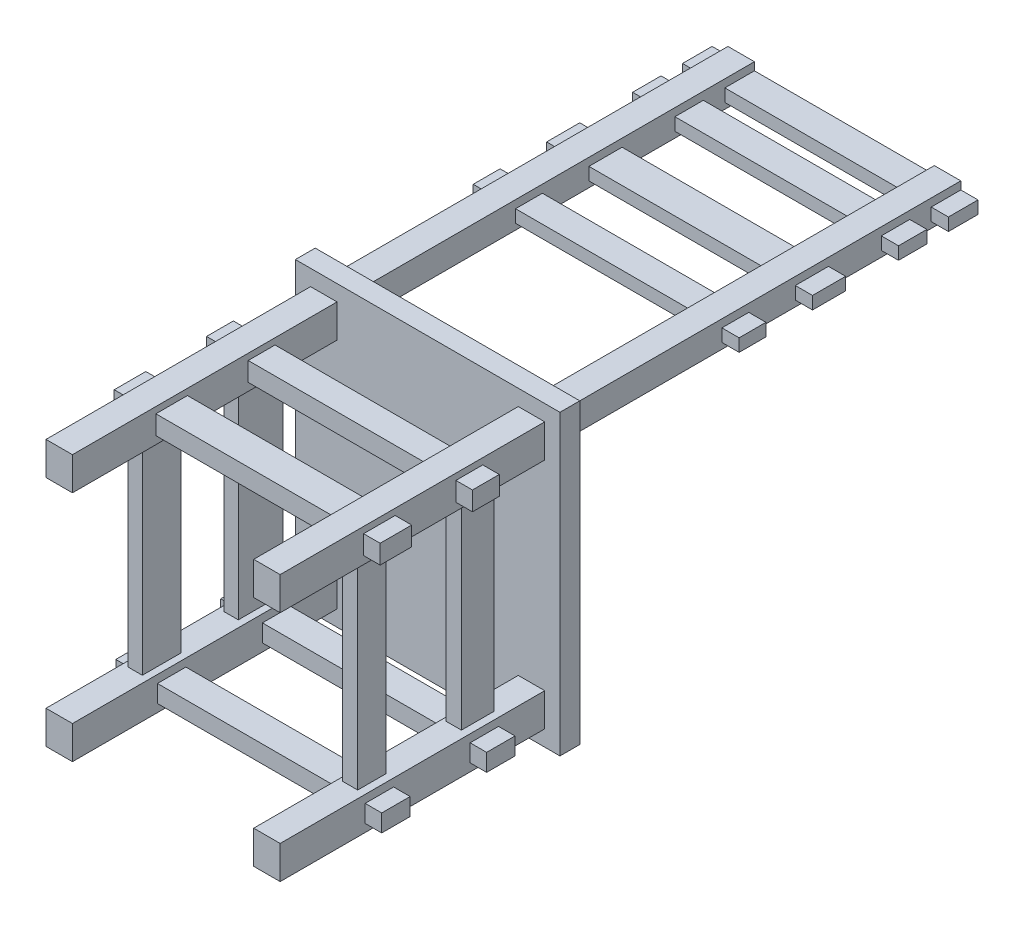
SolidWorks part; units mm, degrees
material "Oak"
ref_plane "Front Plane" through (0, 0, 0) normal (0, 0, 1) x (1, 0, 0)
ref_plane "Top Plane" through (0, 0, 0) normal (0, 1, 0) x (1, 0, 0)
ref_plane "Right Plane" through (0, 0, 0) normal (1, 0, 0) x (0, 0, -1)
sketch "Sketch2" plane through (0, 0, 0) normal (0, 0, 1) x (1, 0, 0)
  line L1 (0, 0) -> (400, 0)
  line L2 (0, 0) -> (0, 450)
  line L3 (0, 450) -> (400, 450)
  line L4 (400, 0) -> (400, 450)
  dimension "D1" = 400
  dimension "D2" = 450
extrude "Boss-Extrude1" add sketch "Sketch2" along normal blind 30
sketch "Sketch3" plane through (0, 0, 30) normal (0, 0, 1) x (1, 0, 0)
  line L0 (0, 450) -> (0, 0) construction
  line L1 (23, 376) -> (63, 376)
  line L2 (23, 376) -> (23, 426)
  line L3 (23, 426) -> (63, 426)
  line L4 (63, 376) -> (63, 426)
  line L5 (23, 376) -> (63, 426) construction
  line L6 (23, 426) -> (63, 376) construction
  line L7 (337, 376) -> (377, 376)
  line L8 (337, 376) -> (337, 426)
  line L9 (337, 426) -> (377, 426)
  line L10 (377, 376) -> (377, 426)
  line L11 (337, 376) -> (377, 426) construction
  line L12 (337, 426) -> (377, 376) construction
  line L13 (377, 74) -> (337, 74)
  line L14 (377, 74) -> (377, 24)
  line L15 (377, 24) -> (337, 24)
  line L16 (337, 74) -> (337, 24)
  line L17 (377, 74) -> (337, 24) construction
  line L18 (377, 24) -> (337, 74) construction
  line L19 (63, 74) -> (23, 74)
  line L20 (63, 74) -> (63, 24)
  line L21 (63, 24) -> (23, 24)
  line L22 (23, 74) -> (23, 24)
  line L23 (63, 74) -> (23, 24) construction
  line L24 (63, 24) -> (23, 74) construction
  line L25 (400, 0) -> (400, 450) construction
  line L26 (400, 450) -> (0, 450) construction
  line L27 (0, 0) -> (400, 0) construction
  point P0 (43, 401)
  point P5 (357, 401)
  point P10 (357, 49)
  point P15 (43, 49)
  dimension "D1" = 23
  dimension "D2" = 23
  dimension "D3" = 23
  dimension "D4" = 23
  dimension "D5" = 24
  dimension "D6" = 24
  dimension "D7" = 24
  dimension "D8" = 24
  dimension "D9" = 40
  dimension "D10" = 40
  dimension "D11" = 50
  dimension "D12" = 40
  dimension "D13" = 50
  dimension "D14" = 40
extrude "Boss-Extrude2" add sketch "Sketch3" along normal blind 400
sketch "Sketch4" plane through (0, 0, 0) normal (0, 0, -1) x (-1, 0, 0)
  line L0 (-400, 0) -> (-400, 450) construction
  line L1 (-376, 426) -> (-336, 426)
  line L2 (-376, 426) -> (-376, 386)
  line L3 (-376, 386) -> (-336, 386)
  line L4 (-336, 426) -> (-336, 386)
  line L5 (-376, 426) -> (-336, 386) construction
  line L6 (-376, 386) -> (-336, 426) construction
  line L7 (-64, 426) -> (-24, 426)
  line L8 (-64, 426) -> (-64, 386)
  line L9 (-64, 386) -> (-24, 386)
  line L10 (-24, 426) -> (-24, 386)
  line L11 (-64, 426) -> (-24, 386) construction
  line L12 (-64, 386) -> (-24, 426) construction
  line L13 (-400, 450) -> (0, 450) construction
  line L14 (0, 450) -> (0, 0) construction
  point P0 (-356, 406)
  point P5 (-44, 406)
  point P14 (-24, 406)
  dimension "D1" = 24
  dimension "D2" = 24
  dimension "D3" = 24
  dimension "D4" = 24
  dimension "D5" = 40
  dimension "D6" = 40
  dimension "D7" = 40
  dimension "D8" = 40
extrude "Boss-Extrude3" add sketch "Sketch4" along normal blind 600
sketch "Sketch5" plane through (0, 0, 0) normal (1, 0, 0) x (0, 0, -1)
  line L1 (-164.3037, 416.4509) -> (-123.7471, 416.4509)
  line L2 (-164.3037, 416.4509) -> (-164.3037, 387.8227)
  line L3 (-164.3037, 387.8227) -> (-123.7471, 387.8227)
  line L4 (-123.7471, 416.4509) -> (-123.7471, 387.8227)
  line L5 (-164.3037, 416.4509) -> (-123.7471, 387.8227) construction
  line L6 (-164.3037, 387.8227) -> (-123.7471, 416.4509) construction
  line L7 (-256.1524, 416.4509) -> (-303.866, 416.4509)
  line L8 (-256.1524, 416.4509) -> (-256.1524, 387.8227)
  line L9 (-256.1524, 387.8227) -> (-303.866, 387.8227)
  line L10 (-303.866, 416.4509) -> (-303.866, 387.8227)
  line L11 (-256.1524, 416.4509) -> (-303.866, 387.8227) construction
  line L12 (-256.1524, 387.8227) -> (-303.866, 416.4509) construction
  point P0 (-144.0254, 402.1368)
  point P5 (-280.0092, 402.1368)
extrude "Boss-Extrude4" add sketch "Sketch5" along normal blind 402
sketch "Sketch6" plane through (0, 0, 0) normal (1, 0, 0) x (0, 0, -1)
  line L1 (-258.5381, 35.9348) -> (-301.4804, 35.9348)
  line L2 (-258.5381, 35.9348) -> (-258.5381, 62.1773)
  line L3 (-258.5381, 62.1773) -> (-301.4804, 62.1773)
  line L4 (-301.4804, 35.9348) -> (-301.4804, 62.1773)
  line L5 (-258.5381, 35.9348) -> (-301.4804, 62.1773) construction
  line L6 (-258.5381, 62.1773) -> (-301.4804, 35.9348) construction
  line L7 (-142.8326, 35.9348) -> (-99.8903, 35.9348)
  line L8 (-142.8326, 35.9348) -> (-142.8326, 62.1773)
  line L9 (-142.8326, 62.1773) -> (-99.8903, 62.1773)
  line L10 (-99.8903, 35.9348) -> (-99.8903, 62.1773)
  line L11 (-142.8326, 35.9348) -> (-99.8903, 62.1773) construction
  line L12 (-142.8326, 62.1773) -> (-99.8903, 35.9348) construction
  point P0 (-280.0092, 49.056)
  point P5 (-121.3614, 49.056)
extrude "Boss-Extrude5" add sketch "Sketch6" along normal blind 402
sketch "Sketch7" plane through (0, 0, 0) normal (1, 0, 0) x (0, 0, -1)
  line L0 (600, 426) -> (600, 386) construction
  line L1 (238.8764, 394.9798) -> (279.433, 394.9798)
  line L2 (238.8764, 394.9798) -> (238.8764, 414.0652)
  line L3 (238.8764, 414.0652) -> (279.433, 414.0652)
  line L4 (279.433, 394.9798) -> (279.433, 414.0652)
  line L5 (238.8764, 394.9798) -> (279.433, 414.0652) construction
  line L6 (238.8764, 414.0652) -> (279.433, 394.9798) construction
  line L7 (349.8106, 394.9798) -> (399.9099, 394.9798)
  line L8 (349.8106, 394.9798) -> (349.8106, 414.0652)
  line L9 (349.8106, 414.0652) -> (399.9099, 414.0652)
  line L10 (399.9099, 394.9798) -> (399.9099, 414.0652)
  line L11 (349.8106, 394.9798) -> (399.9099, 414.0652) construction
  line L12 (349.8106, 414.0652) -> (399.9099, 394.9798) construction
  line L13 (479.8302, 394.9798) -> (522.7725, 394.9798)
  line L14 (479.8302, 394.9798) -> (479.8302, 414.0652)
  line L15 (479.8302, 414.0652) -> (522.7725, 414.0652)
  line L16 (522.7725, 394.9798) -> (522.7725, 414.0652)
  line L17 (479.8302, 394.9798) -> (522.7725, 414.0652) construction
  line L18 (479.8302, 414.0652) -> (522.7725, 394.9798) construction
  line L19 (555.2863, 394.9798) -> (600, 394.9798)
  line L20 (555.2863, 394.9798) -> (555.2863, 414.0652)
  line L21 (555.2863, 414.0652) -> (600, 414.0652)
  line L22 (600, 394.9798) -> (600, 414.0652)
  line L23 (555.2863, 394.9798) -> (600, 414.0652) construction
  line L24 (555.2863, 414.0652) -> (600, 394.9798) construction
  point P0 (259.1547, 404.5225)
  point P5 (374.8603, 404.5225)
  point P10 (501.3014, 404.5225)
  point P15 (577.6432, 404.5225)
extrude "Boss-Extrude6" add sketch "Sketch7" along normal blind 402
sketch "Sketch8" plane through (0, 74, 0) normal (0, 1, 0) x (1, 0, 0)
  line L1 (31.0506, -168.9347) -> (52.6621, -168.9347)
  line L2 (31.0506, -168.9347) -> (31.0506, -101.013)
  line L3 (31.0506, -101.013) -> (52.6621, -101.013)
  line L4 (52.6621, -168.9347) -> (52.6621, -101.013)
  line L5 (31.0506, -168.9347) -> (52.6621, -101.013) construction
  line L6 (31.0506, -101.013) -> (52.6621, -168.9347) construction
  line L7 (31.0506, -314.0403) -> (52.6621, -314.0403)
  line L8 (31.0506, -314.0403) -> (31.0506, -255.3806)
  line L9 (31.0506, -255.3806) -> (52.6621, -255.3806)
  line L10 (52.6621, -314.0403) -> (52.6621, -255.3806)
  line L11 (31.0506, -314.0403) -> (52.6621, -255.3806) construction
  line L12 (31.0506, -255.3806) -> (52.6621, -314.0403) construction
  point P0 (41.8563, -134.9738)
  point P5 (41.8563, -284.7104)
extrude "Boss-Extrude7" add sketch "Sketch8" along normal up to next and the other way blind 2
sketch "Sketch9" plane through (0, 376, 0) normal (0, -1, 0) x (1, 0, 0)
  line L1 (342.5914, 258.565) -> (365.7013, 258.565)
  line L2 (342.5914, 258.565) -> (342.5914, 301.4834)
  line L3 (342.5914, 301.4834) -> (365.7013, 301.4834)
  line L4 (365.7013, 258.565) -> (365.7013, 301.4834)
  line L5 (342.5914, 258.565) -> (365.7013, 301.4834) construction
  line L6 (342.5914, 301.4834) -> (365.7013, 258.565) construction
  line L7 (342.5914, 95.1449) -> (365.7013, 95.1449)
  line L8 (342.5914, 95.1449) -> (342.5914, 144.6661)
  line L9 (342.5914, 144.6661) -> (365.7013, 144.6661)
  line L10 (365.7013, 95.1449) -> (365.7013, 144.6661)
  line L11 (342.5914, 95.1449) -> (365.7013, 144.6661) construction
  line L12 (342.5914, 144.6661) -> (365.7013, 95.1449) construction
  point P0 (354.1463, 280.0242)
  point P5 (354.1463, 119.9055)
extrude "Boss-Extrude8" add sketch "Sketch9" along normal up to next
